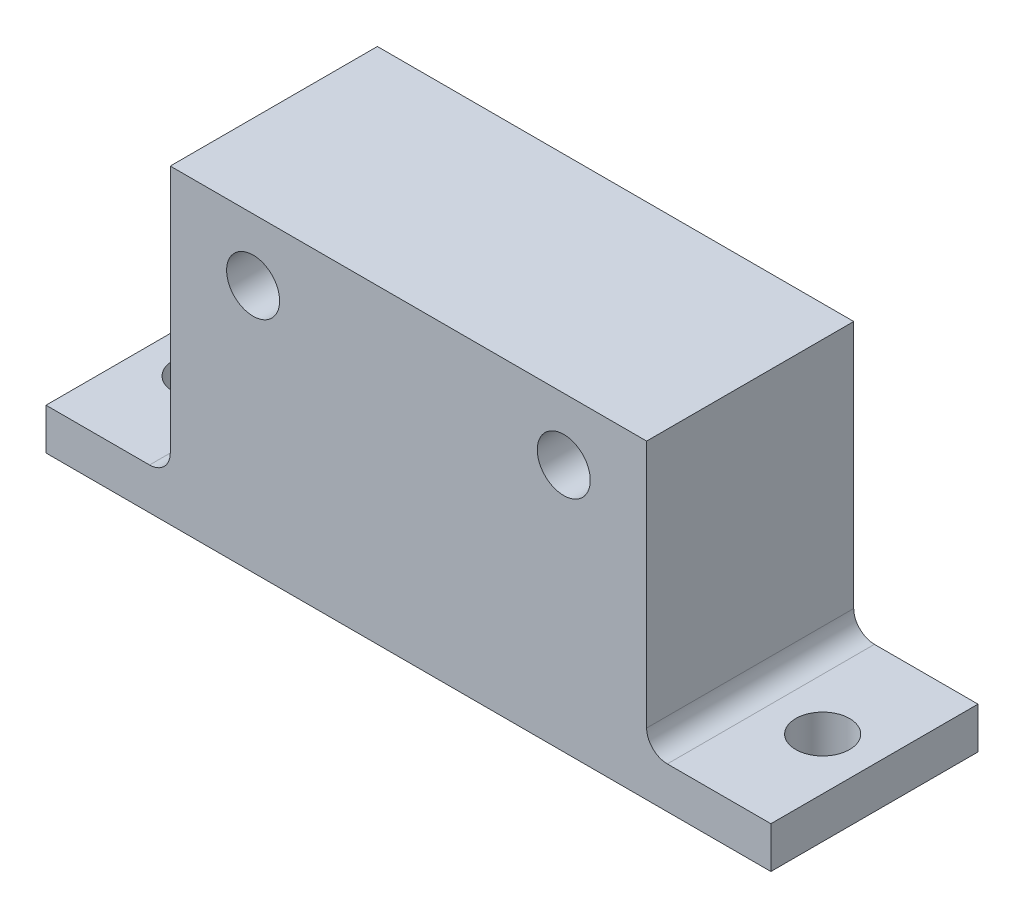
SolidWorks part; units mm, degrees
material "ABS"
ref_plane "Front Plane" through (0, 0, 0) normal (0, 0, 1) x (1, 0, 0)
ref_plane "Top Plane" through (0, 0, 0) normal (0, 1, 0) x (1, 0, 0)
ref_plane "Right Plane" through (0, 0, 0) normal (1, 0, 0) x (0, 0, -1)
sketch "Sketch1" plane through (0, 0, 0) normal (0, 0, 1) x (1, 0, 0)
  line L1 (-22.225, -9.525) -> (22.225, -9.525)
  line L2 (-22.225, -9.525) -> (-22.225, 9.525)
  line L3 (-22.225, 9.525) -> (22.225, 9.525)
  line L4 (22.225, -9.525) -> (22.225, 9.525)
  line L5 (-22.225, -9.525) -> (22.225, 9.525) construction
  line L6 (-22.225, 9.525) -> (22.225, -9.525) construction
  point P0 (0, 0)
  dimension "D1" = 44.45
  dimension "D2" = 19.05
extrude "Boss-Extrude1" add sketch "Sketch1" along normal blind 12.7
sketch "Sketch2" plane through (0, 0, 12.7) normal (0, 0, 1) x (1, 0, 0)
  line L0 (-22.225, -9.525) -> (22.225, -9.525) construction
  line L1 (-22.225, 9.525) -> (-14.605, 9.525)
  line L2 (-22.225, 9.525) -> (-22.225, -6.985)
  line L3 (-22.225, -6.985) -> (-14.605, -6.985)
  line L4 (-14.605, 9.525) -> (-14.605, -6.985)
  line L5 (22.225, 9.525) -> (14.605, 9.525)
  line L6 (22.225, 9.525) -> (22.225, -6.985)
  line L7 (22.225, -6.985) -> (14.605, -6.985)
  line L8 (14.605, 9.525) -> (14.605, -6.985)
  dimension "D1" = 7.62
  dimension "D2" = 7.62
  dimension "D3" = 2.54
  dimension "D4" = 2.54
extrude "Cut-Extrude1" cut sketch "Sketch2" against normal blind 12.7
fillet "Fillet1" radius 1.27 1 edges at (-14.605, -6.985, 6.35)
fillet "Fillet2" radius 1.27 1 edges at (14.605, -6.985, 6.35)
sketch "Sketch3" plane through (0, 0, 0) normal (0, 0, -1) x (-1, 0, 0)
  line L0 (-14.605, 9.525) -> (14.605, 9.525) construction
  circle A0 centre (-9.525, 5.715) radius 1.6256
  circle A1 centre (9.525, 5.715) radius 1.6256
  dimension "D1" = 3.2512
  dimension "D2" = 3.2512
  dimension "D3" = 9.525
  dimension "D4" = 9.525
  dimension "D5" = 3.81
  dimension "D6" = 3.81
extrude "Cut-Extrude2" cut sketch "Sketch3" against normal blind 12.7
sketch "Sketch4" plane through (0, -6.985, 0) normal (0, 1, 0) x (1, 0, 0)
  line L0 (22.225, 0) -> (22.225, -12.7) construction
  line L1 (15.875, 0) -> (22.225, 0) construction
  line L2 (-22.225, 0) -> (-15.875, 0) construction
  line L3 (-22.225, 0) -> (-22.225, -12.7) construction
  circle A0 centre (19.05, -6.35) radius 1.651
  circle A1 centre (-19.05, -6.4262) radius 1.651
  dimension "D1" = 3.302
  dimension "D2" = 3.302
  dimension "D3" = 3.175
  dimension "D4" = 6.35
  dimension "D5" = 6.4262
  dimension "D6" = 3.175
extrude "Cut-Extrude3" cut sketch "Sketch4" against normal blind 12.7
